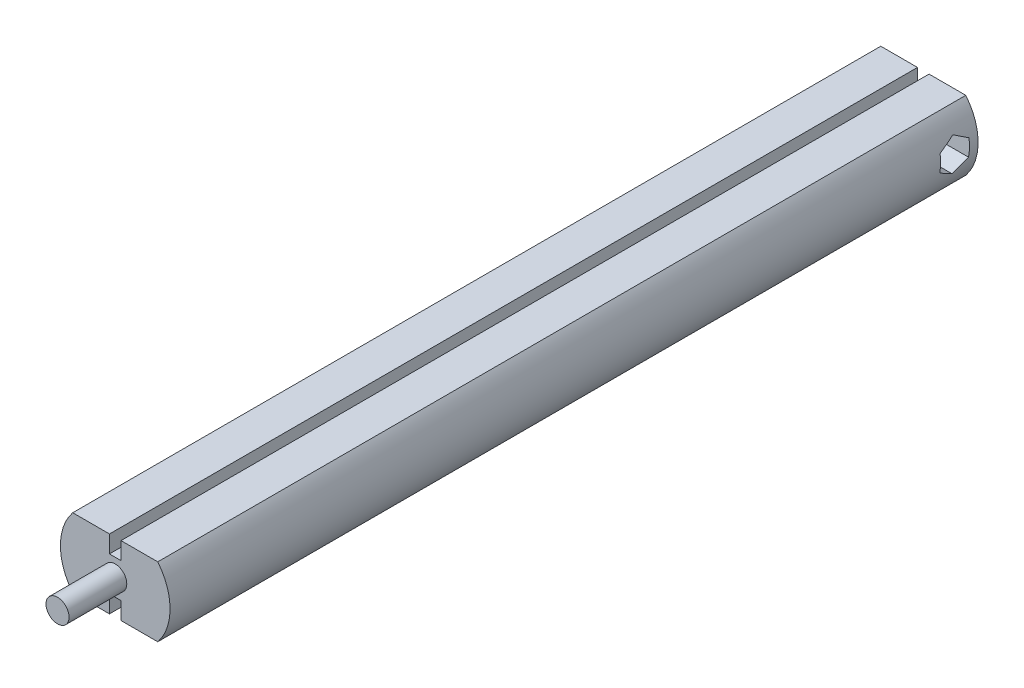
SolidWorks part; units mm, degrees
material "ABS"
ref_plane "Front Plane" through (0, 0, 0) normal (0, 0, 1) x (1, 0, 0)
ref_plane "Top Plane" through (0, 0, 0) normal (0, 1, 0) x (1, 0, 0)
ref_plane "Right Plane" through (0, 0, 0) normal (1, 0, 0) x (0, 0, -1)
sketch "Sketch1" plane through (0, 0, 0) normal (0, 0, 1) x (1, 0, 0)
  circle A0 centre (0, 0) radius 4.75
  dimension "D1" = 9.5
extrude "Boss-Extrude1" add sketch "Sketch1" along normal blind 70
sketch "Sketch2" plane through (0, 0, 0) normal (0, 0, -1) x (-1, 0, 0)
  line L0 (1.8, 0) -> (-0.94, 0) construction
  line L1 (-0.94, 1.5351) -> (-0.94, -1.5351)
  arc A0 (-0.94, -1.5351) -> (-0.94, 1.5351) centre (0, 0) ccw
  point P7 (-0.94, 0)
  dimension "D1" = 3.6
  dimension "D2" = 2.74
extrude "Cut-Extrude1" cut sketch "Sketch2" against normal blind 10
sketch "Sketch3" plane through (0.94, 0, 0) normal (-1, 0, 0) x (0, 0, 1)
  line L0 (0, 1.5351) -> (0, -1.5351) construction
  line L1 (3.2307, 0.7541) -> (1.9623, 1.4429)
  line L2 (1.9623, 1.4429) -> (0.7316, 0.6888)
  line L3 (0.7316, 0.6888) -> (0.7693, -0.7541)
  line L4 (0.7693, -0.7541) -> (2.0377, -1.4429)
  line L5 (2.0377, -1.4429) -> (3.2684, -0.6888)
  line L6 (3.2684, -0.6888) -> (3.2307, 0.7541)
  line L8 (0, 0) -> (2, 0) construction
  circle A1 centre (2, 0) radius 1.25 construction
  dimension "D1" = 2.5
  dimension "D2" = 2
  dimension "D3" = 1.4429
extrude "Cut-Extrude2" cut sketch "Sketch3" against normal through all
sketch "Sketch4" plane through (0, 0, 0) normal (0, 0, -1) x (-1, 0, 0)
  line L0 (-3.6827, 3) -> (3.6827, 3)
  line L1 (-3.6827, -3) -> (3.6827, -3)
  circle A0 centre (0, 0) radius 4.75 construction
  arc A1 (-3.6827, -3) -> (3.6827, -3) centre (0, 0) ccw
  arc A2 (3.6827, 3) -> (-3.6827, 3) centre (0, 0) ccw
  dimension "D1" = 3
  dimension "D2" = 3
extrude "Cut-Extrude3" cut sketch "Sketch4" against normal up to next
sketch "Sketch5" plane through (0, 3, 0) normal (0, 1, 0) x (1, 0, 0)
  line L0 (0, 0) -> (0, -70) construction
  line L1 (3.6827, -70) -> (-3.6827, -70) construction
  line L2 (3.6827, 0) -> (-3.6827, 0) construction
  line L3 (-0.5, -70) -> (0.5, -70)
  line L4 (-0.5, -70) -> (-0.5, 0)
  line L5 (-0.5, 0) -> (0.5, 0)
  line L6 (0.5, -70) -> (0.5, 0)
  line L7 (-0.5, -70) -> (0.5, 0) construction
  line L8 (-0.5, 0) -> (0.5, -70) construction
  point P5 (0, -35)
  dimension "D1" = 1
extrude "Cut-Extrude4" cut sketch "Sketch5" against normal blind 1.5
mirror "Mirror1" about plane through (0, 0, 0) normal (0, 1, 0) of "Cut-Extrude4"
sketch "Sketch6" plane through (0, 0, 70) normal (0, 0, 1) x (1, 0, 0)
  line L0 (-4.75, 0) -> (4.75, 0) construction
  line L1 (0, 1.5) -> (0, -1.5) construction
  line L2 (-0.5, 1.5) -> (0.5, 1.5) construction
  line L3 (-0.5, -1.5) -> (0.5, -1.5) construction
  arc A0 (-3.6827, 3) -> (-3.6827, -3) centre (0, 0) ccw construction
  arc A1 (3.6827, -3) -> (3.6827, 3) centre (0, 0) ccw construction
  circle A2 centre (0, 0) radius 1
  dimension "D1" = 2
extrude "Boss-Extrude2" add sketch "Sketch6" along normal blind 5
